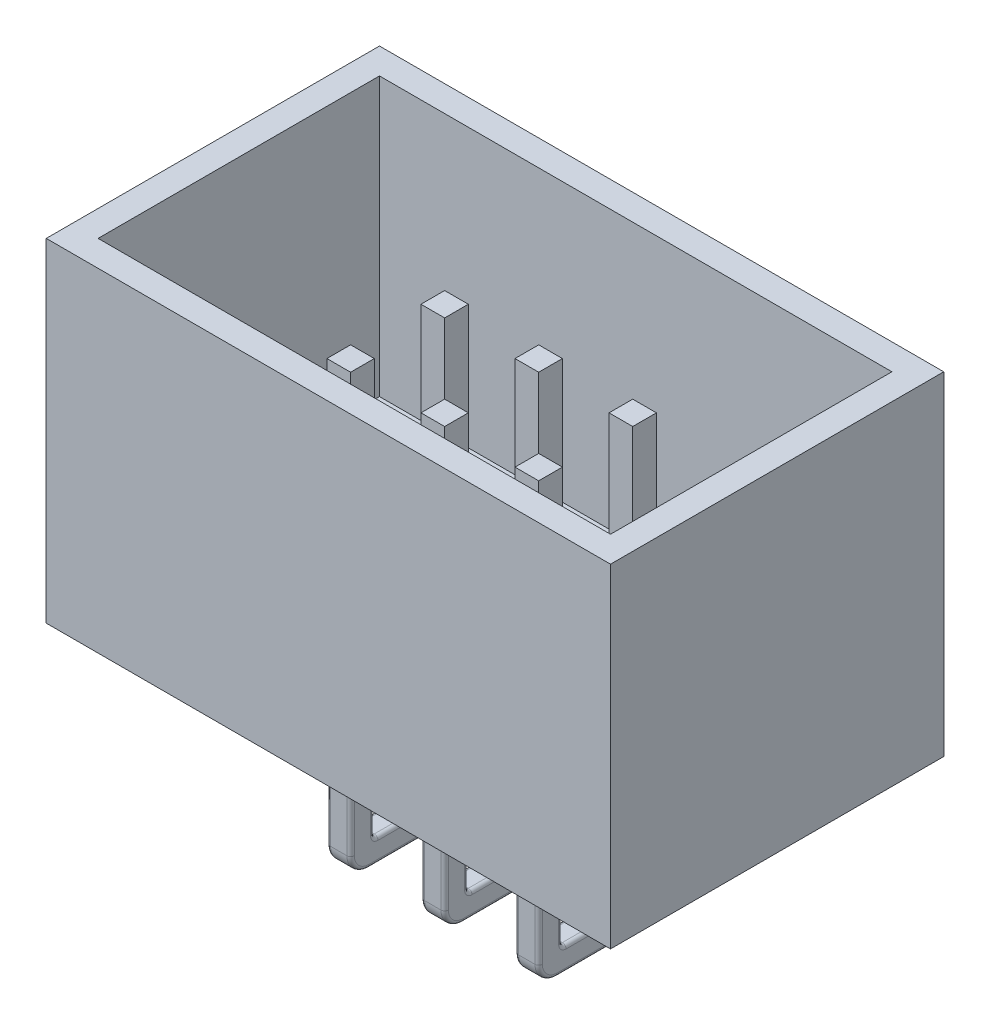
SolidWorks part; units mm, degrees
ref_plane "Ebene vorne" through (0, 0, 0) normal (0, 0, 1) x (1, 0, 0)
ref_plane "Ebene oben" through (0, 0, 0) normal (0, 1, 0) x (1, 0, 0)
ref_plane "Ebene rechts" through (0, 0, 0) normal (1, 0, 0) x (0, 0, -1)
sketch "Skizze1" plane through (0, 0, 0) normal (0, 0, 1) x (1, 0, 0)
  line L0 (-7.62, 10.922) -> (7.62, 10.922)
  line L1 (7.62, 10.922) -> (7.62, 1.922)
  line L2 (7.62, 1.922) -> (-7.62, 1.922)
  line L3 (-7.62, 1.922) -> (-7.62, 10.922)
  dimension "D1" = 9
  dimension "D2" = 15.24
extrude "Component_Outline" add sketch "Skizze1" along normal blind 9 separate body
sketch3d "3D-Skizze1"
  line L0 (0, 0, 0) -> (1, 0, 0)
  line L1 (0, 0, 0) -> (0, 1, 0)
  line L2 (0, 0, 0) -> (0, 0, 1)
  point P0 (0, 0, 0)
sketch "Skizze2" plane through (0, 10.922, 0) normal (0, 1, 0) x (1, 0, 0)
  line L8 (6.92, -0.7) -> (-6.92, -0.7)
  line L9 (-6.92, -0.7) -> (-6.92, -8.3)
  line L10 (-6.92, -8.3) -> (6.92, -8.3)
  line L11 (6.92, -8.3) -> (6.92, -0.7)
  line L12 (6.92, -0.7) -> (-6.92, -0.7)
  line L13 (-6.92, -0.7) -> (-6.92, -8.3)
  line L14 (-6.92, -8.3) -> (6.92, -8.3)
  line L15 (6.92, -8.3) -> (6.92, -0.7)
  dimension "D1" = 0.7
extrude "Schnitt-Linear austragen1" cut sketch "Skizze2" against normal offset from surface (7.5 mm away) 1.5 up to face at (0, 1.922, 4.5)
sketch "Skizze3" plane through (0, 1.922, 0) normal (0, -1, 0) x (1, 0, 0)
  line L0 (-7.62, 0) -> (7.62, 0) construction
  line L1 (-0.32, 3) -> (0.32, 3)
  line L2 (-0.32, 3) -> (-0.32, 3.64)
  line L3 (-0.32, 3.64) -> (0.32, 3.64)
  line L4 (0.32, 3) -> (0.32, 3.64)
  line L5 (-0.32, 3) -> (0.32, 3.64) construction
  line L6 (-0.32, 3.64) -> (0.32, 3) construction
  line L7 (-0.32, 5.54) -> (0.32, 5.54)
  line L8 (-0.32, 5.54) -> (-0.32, 6.18)
  line L9 (-0.32, 6.18) -> (0.32, 6.18)
  line L10 (0.32, 5.54) -> (0.32, 6.18)
  line L11 (-0.32, 5.54) -> (0.32, 6.18) construction
  line L12 (-0.32, 6.18) -> (0.32, 5.54) construction
  line L13 (-2.86, 3) -> (-2.22, 3)
  line L14 (-2.86, 3) -> (-2.86, 3.64)
  line L15 (-2.86, 3.64) -> (-2.22, 3.64)
  line L16 (-2.22, 3) -> (-2.22, 3.64)
  line L17 (-2.86, 3) -> (-2.22, 3.64) construction
  line L18 (-2.86, 3.64) -> (-2.22, 3) construction
  line L19 (-2.86, 5.54) -> (-2.22, 5.54)
  line L20 (-2.86, 5.54) -> (-2.86, 6.18)
  line L21 (-2.86, 6.18) -> (-2.22, 6.18)
  line L22 (-2.22, 5.54) -> (-2.22, 6.18)
  line L23 (-2.86, 5.54) -> (-2.22, 6.18) construction
  line L24 (-2.86, 6.18) -> (-2.22, 5.54) construction
  line L25 (2.22, 3) -> (2.86, 3)
  line L26 (2.22, 3) -> (2.22, 3.64)
  line L27 (2.22, 3.64) -> (2.86, 3.64)
  line L28 (2.86, 3) -> (2.86, 3.64)
  line L29 (2.22, 3) -> (2.86, 3.64) construction
  line L30 (2.22, 3.64) -> (2.86, 3) construction
  line L31 (2.22, 5.54) -> (2.86, 5.54)
  line L32 (2.22, 5.54) -> (2.22, 6.18)
  line L33 (2.22, 6.18) -> (2.86, 6.18)
  line L34 (2.86, 5.54) -> (2.86, 6.18)
  line L35 (2.22, 5.54) -> (2.86, 6.18) construction
  line L36 (2.22, 6.18) -> (2.86, 5.54) construction
  point P0 (0, 3.32)
  point P7 (0, 5.86)
  point P12 (-2.54, 3.32)
  point P17 (-2.54, 5.86)
  point P22 (2.54, 3.32)
  point P27 (2.54, 5.86)
  dimension "D1" = 0.64
  dimension "D2" = 0.64
  dimension "D3" = 3.32
  dimension "D4" = 0.64
  dimension "D5" = 0.64
  dimension "D6" = 2.54
  dimension "D7" = 0.64
  dimension "D8" = 0.64
  dimension "D9" = 0.64
  dimension "D10" = 0.64
  dimension "D11" = 2.54
  dimension "D12" = 2.54
  dimension "D13" = 3.32
  dimension "D14" = 0.64
  dimension "D15" = 0.64
  dimension "D16" = 0.64
  dimension "D17" = 0.64
  dimension "D18" = 2.54
  dimension "D19" = 2.54
  dimension "D20" = 3.32
extrude "Aufsatz-Linear austragen1" add sketch "Skizze3" along normal blind 2.16 and the other way offset from surface (7.16 mm away) 1.84 other way up to face at (0, 10.922, 4.5)
sketch "Skizze4" plane through (0, 0, 3) normal (0, 0, -1) x (-1, 0, 0)
  line L0 (2.22, -0.238) -> (2.22, 1.922) construction
  line L1 (2.86, -0.238) -> (2.22, -0.238)
  line L2 (2.86, -0.238) -> (2.86, 0.402)
  line L3 (2.86, 0.402) -> (2.22, 0.402)
  line L4 (2.22, -0.238) -> (2.22, 0.402)
  line L5 (-0.32, -0.238) -> (-0.32, 1.922) construction
  line L6 (0.32, -0.238) -> (-0.32, -0.238)
  line L7 (0.32, -0.238) -> (0.32, 0.402)
  line L8 (0.32, 0.402) -> (-0.32, 0.402)
  line L9 (-0.32, -0.238) -> (-0.32, 0.402)
  line L10 (-2.86, -0.238) -> (-2.86, 1.922) construction
  line L11 (-2.22, -0.238) -> (-2.86, -0.238)
  line L12 (-2.22, -0.238) -> (-2.22, 0.402)
  line L13 (-2.22, 0.402) -> (-2.86, 0.402)
  line L14 (-2.86, -0.238) -> (-2.86, 0.402)
  dimension "D1" = 0.64
sketch "Skizze5" plane through (0, -0.238, 0) normal (0, -1, 0) x (1, 0, 0)
  line L4 (-2.22, 5.54) -> (-2.22, 6.18)
  line L5 (-2.22, 6.18) -> (-2.86, 6.18)
  line L6 (-2.86, 6.18) -> (-2.86, 5.54)
  line L7 (-2.86, 5.54) -> (-2.22, 5.54)
  line L8 (-2.22, 5.54) -> (-2.22, 6.18)
  line L9 (-2.22, 6.18) -> (-2.86, 6.18)
  line L10 (-2.86, 6.18) -> (-2.86, 5.54)
  line L11 (-2.86, 5.54) -> (-2.22, 5.54)
  line L12 (0.32, 5.54) -> (0.32, 6.18)
  line L13 (0.32, 6.18) -> (-0.32, 6.18)
  line L14 (-0.32, 6.18) -> (-0.32, 5.54)
  line L15 (-0.32, 5.54) -> (0.32, 5.54)
  line L16 (0.32, 5.54) -> (0.32, 6.18)
  line L17 (0.32, 6.18) -> (-0.32, 6.18)
  line L18 (-0.32, 6.18) -> (-0.32, 5.54)
  line L19 (-0.32, 5.54) -> (0.32, 5.54)
  line L20 (2.86, 5.54) -> (2.86, 6.18)
  line L21 (2.86, 6.18) -> (2.22, 6.18)
  line L22 (2.22, 6.18) -> (2.22, 5.54)
  line L23 (2.22, 5.54) -> (2.86, 5.54)
  line L24 (2.86, 5.54) -> (2.86, 6.18)
  line L25 (2.86, 6.18) -> (2.22, 6.18)
  line L26 (2.22, 6.18) -> (2.22, 5.54)
  line L27 (2.22, 5.54) -> (2.86, 5.54)
  dimension "D1" = 0
  dimension "D2" = 0
  dimension "D3" = 0
extrude "Aufsatz-Linear austragen2" add sketch "Skizze5" along normal blind 2.54
extrude "Aufsatz-Linear austragen3" add sketch "Skizze4" along normal offset from surface (6 mm away) 3 up to face at (0, 6.422, 0) offset beyond the face yes
sketch "Skizze6" plane through (0, 0, 5.54) normal (0, 0, -1) x (-1, 0, 0)
  line L0 (2.22, -2.778) -> (2.22, 1.922) construction
  line L1 (2.86, -2.778) -> (2.22, -2.778)
  line L2 (2.86, -2.778) -> (2.86, -2.138)
  line L3 (2.86, -2.138) -> (2.22, -2.138)
  line L4 (2.22, -2.778) -> (2.22, -2.138)
  line L5 (-0.32, -2.778) -> (-0.32, 1.922) construction
  line L6 (0.32, -2.778) -> (-0.32, -2.778)
  line L7 (0.32, -2.778) -> (0.32, -2.138)
  line L8 (0.32, -2.138) -> (-0.32, -2.138)
  line L9 (-0.32, -2.778) -> (-0.32, -2.138)
  line L10 (-2.86, -2.778) -> (-2.86, 1.922) construction
  line L11 (-2.22, -2.778) -> (-2.86, -2.778)
  line L12 (-2.22, -2.778) -> (-2.22, -2.138)
  line L13 (-2.22, -2.138) -> (-2.86, -2.138)
  line L14 (-2.86, -2.778) -> (-2.86, -2.138)
  dimension "D1" = 0.64
extrude "Aufsatz-Linear austragen4" add sketch "Skizze6" along normal up to surface (8.54 mm away) up to face at (2.54, 0.082, -3)
fillet "Verrundung1" radius 0.5 6 edges at (-2.54, -2.778, 6.18) (0, -2.778, 6.18) (2.54, -2.778, 6.18) (2.54, -0.238, 3.64) (0, -0.238, 3.64) (-2.54, -0.238, 3.64)
ref_plane "Ebene1" through (0, -1.17, 0) normal (0, 1, 0) x (1, 0, 0)
ref_point "Punkt1"
fillet "Verrundung2" radius 0.1 114 edges at (2.86, 1.092, 3.64) (2.86, 1.922, 3.32) (2.86, 1.162, 3) (2.54, 1.922, 3) (2.22, 1.162, 3) (2.22, 1.922, 3.32) (2.22, 1.092, 3.64) (2.54, 1.922, 3.64) (2.86, -0.238, 0.07) (2.86, -0.178, 6.18) (2.86, 1.922, 5.86) (2.86, -0.108, 5.54) (2.54, 1.922, 5.54) (2.22, -0.108, 5.54) (2.22, 1.922, 5.86) (2.22, -0.178, 6.18) (2.54, 1.922, 6.18) (-2.22, -2.778, 1.34) (0.32, -2.778, 1.34) (2.86, -2.778, 1.34) (-2.86, 0.402, 0) (-2.54, 0.402, 3) (-2.22, 0.402, 0) (-2.54, -0.238, -3) (-2.86, 0.082, -3) (-2.54, 0.402, -3) (-2.22, 0.082, -3) (-0.32, 0.402, 0) (0, 0.402, 3) (0.32, 0.402, 0) (0, -0.238, -3) (-0.32, 0.082, -3) (0, 0.402, -3) (0.32, 0.082, -3) (2.22, 0.402, 0) (2.54, 0.402, 3) (2.86, 0.402, 0) (2.54, -0.238, -3) (2.22, 0.082, -3) (2.54, 0.402, -3) (2.86, 0.082, -3) (-2.86, -2.138, 1.27) (-2.54, -2.138, 5.54) (-2.22, -2.138, 1.27) (-2.54, -2.778, -3) (-2.86, -2.458, -3) (-2.54, -2.138, -3) (-2.22, -2.458, -3) (-0.32, -2.138, 1.27) (0, -2.138, 5.54) (0.32, -2.138, 1.27) (0, -2.778, -3) (-0.32, -2.458, -3) (0, -2.138, -3) (0.32, -2.458, -3) (2.22, -2.138, 1.27) (2.54, -2.138, 5.54) (2.86, -2.138, 1.27) (2.54, -2.778, -3) (2.22, -2.458, -3) (2.54, -2.138, -3) (2.86, -2.458, -3) (-2.86, -2.778, 1.34) (-2.86, -2.6316, 6.0336) (-2.22, -2.6316, 6.0336) (-0.32, -2.778, 1.34) (-0.32, -2.6316, 6.0336) (0.32, -2.6316, 6.0336) (2.22, -2.778, 1.34) (2.22, -2.6316, 6.0336) (2.86, -2.6316, 6.0336) (2.22, -0.238, 0.07) (2.22, -0.0916, 3.4936) (2.86, -0.0916, 3.4936) (-0.32, -0.238, 0.07) (-0.32, -0.0916, 3.4936) (0.32, -0.0916, 3.4936) (-2.86, -0.238, 0.07) (-2.86, -0.0916, 3.4936) (-2.22, -0.0916, 3.4936) (0.32, 1.092, 3.64) (0.32, 1.922, 3.32) (0.32, 1.162, 3) (0, 1.922, 3) (-0.32, 1.162, 3) (-0.32, 1.922, 3.32) (-0.32, 1.092, 3.64) (0, 1.922, 3.64) (0.32, -0.238, 0.07) (0.32, -0.178, 6.18) (0.32, 1.922, 5.86) (0.32, -0.108, 5.54) (0, 1.922, 5.54) (-0.32, -0.108, 5.54) (-0.32, 1.922, 5.86) (-0.32, -0.178, 6.18) (0, 1.922, 6.18) (-2.22, 1.092, 3.64) (-2.22, 1.922, 3.32) (-2.22, 1.162, 3) (-2.54, 1.922, 3) (-2.86, 1.162, 3) (-2.86, 1.922, 3.32) (-2.86, 1.092, 3.64) (-2.54, 1.922, 3.64) (-2.22, -0.238, 0.07) (-2.22, -0.178, 6.18) (-2.22, 1.922, 5.86) (-2.22, -0.108, 5.54) (-2.54, 1.922, 5.54) (-2.86, -0.108, 5.54) (-2.86, 1.922, 5.86) (-2.86, -0.178, 6.18) (-2.54, 1.922, 6.18)
